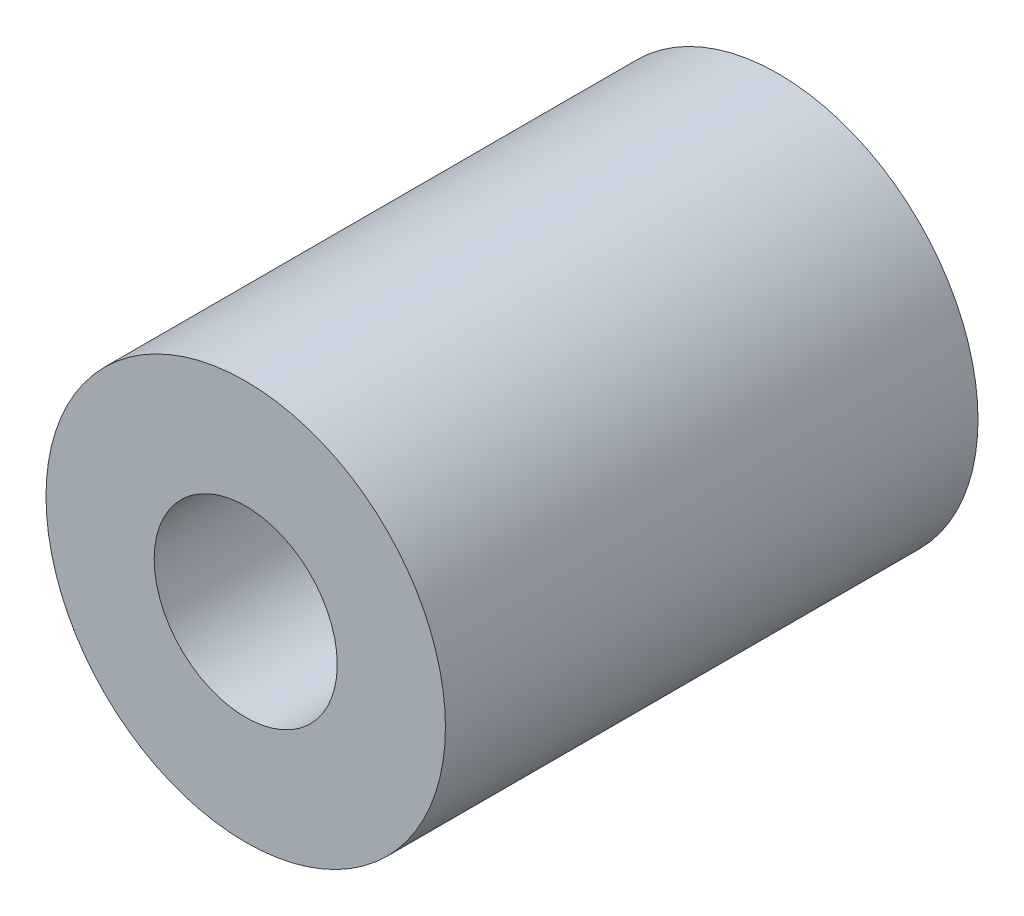
SolidWorks part; units mm, degrees
ref_plane "Front Plane" through (0, 0, 0) normal (0, 0, 1) x (1, 0, 0)
ref_plane "Top Plane" through (0, 0, 0) normal (0, 1, 0) x (1, 0, 0)
ref_plane "Right Plane" through (0, 0, 0) normal (1, 0, 0) x (0, 0, -1)
sketch "Sketch1" plane through (0, 0, 0) normal (0, 0, 1) x (1, 0, 0)
  circle A0 centre (0, 0) radius 3
  circle A1 centre (0, 0) radius 1.375
  dimension "D1" = 6
  dimension "D2" = 2.75
extrude "Boss-Extrude1" add sketch "Sketch1" along normal blind 8
